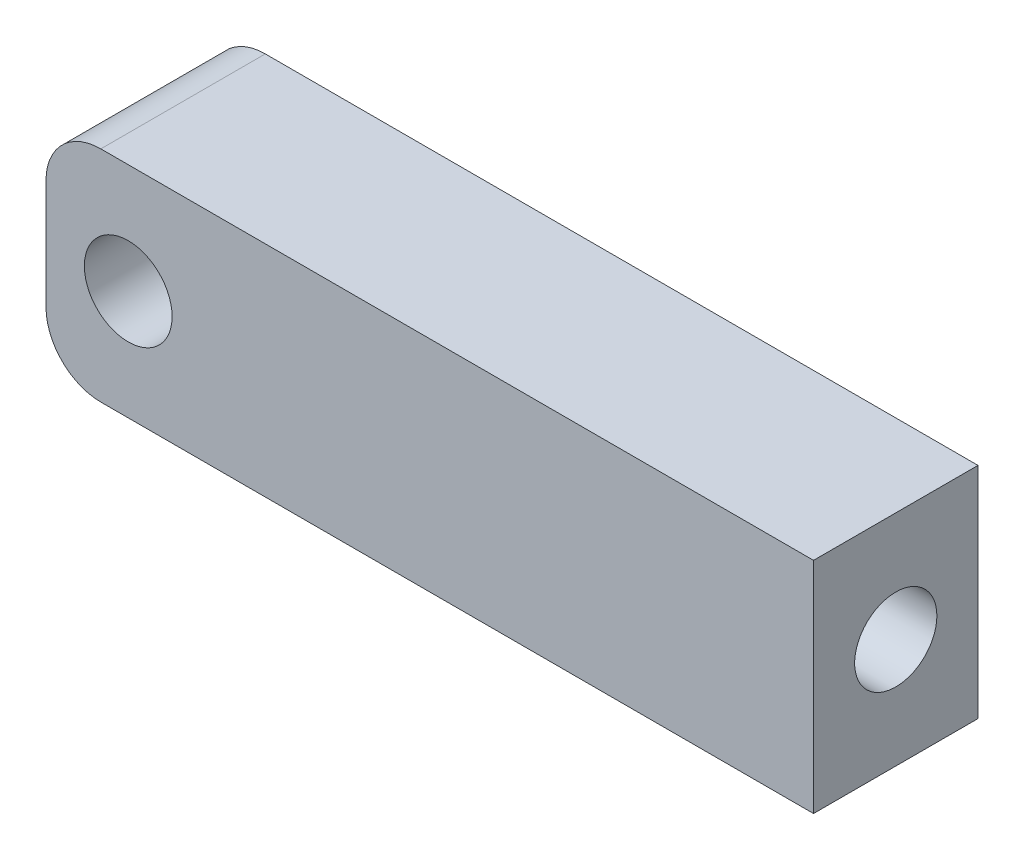
SolidWorks part; units mm, degrees
ref_plane "前视基准面" through (0, 0, 0) normal (0, 0, 1) x (1, 0, 0)
ref_plane "上视基准面" through (0, 0, 0) normal (0, 1, 0) x (1, 0, 0)
ref_plane "右视基准面" through (0, 0, 0) normal (1, 0, 0) x (0, 0, -1)
sketch "草图2" plane through (0, 0, 0) normal (0, 0, 1) x (1, 0, 0)
  line L0 (0, 2) -> (0, 6)
  line L1 (2, 8) -> (28, 8)
  line L2 (28, 8) -> (28, 0)
  line L3 (28, 0) -> (2, 0)
  arc A0 (0, 2) -> (2, 0) centre (2, 2) ccw
  arc A1 (0, 6) -> (2, 8) centre (2, 6) cw
  circle A2 centre (3, 4) radius 1.6
  point P7 (0, 0)
  dimension "D1" = 2
extrude "凸台-拉伸1" add sketch "草图2" along normal blind 6
sketch "草图3" plane through (28, 0, 0) normal (1, 0, 0) x (0, 0, -1)
  circle A0 centre (-3, 4) radius 1.5
  dimension "D1" = 3
extrude "切除-拉伸1" cut sketch "草图3" against normal blind 20
sketch "草图4" plane through (0, 0, 0) normal (0, 0, -1) x (-1, 0, 0)
  circle A0 centre (-3, 4) radius 3.6
  dimension "D1" = 7.2
extrude "切除-拉伸2" cut sketch "草图4" against normal blind 3
